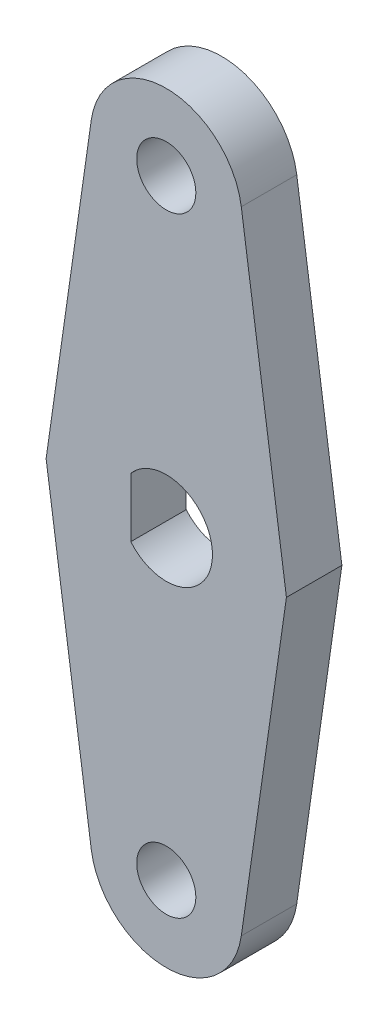
SolidWorks part; units mm, degrees
ref_plane "Alzado" through (0, 0, 0) normal (1, 0, 0) x (0, 1, 0)
ref_plane "Planta" through (0, 0, 0) normal (0, 0, 1) x (0, 1, 0)
ref_plane "Vista lateral" through (0, 0, 0) normal (0, 1, 0) x (-1, 0, 0)
sketch "Croquis1" plane through (0, 0, 0) normal (0, 0, 1) x (0, 1, 0)
  line L0 (-1.6011, 1.92) -> (1.6011, 1.92)
  line L1 (0, 6.5) -> (-17.0801, 4.0588)
  line L2 (0, -6.5) -> (-17.0801, -4.0588)
  line L3 (0, -55) -> (0, 55) construction
  line L4 (0, 6.5) -> (17.0801, 4.0588)
  line L5 (0, -6.5) -> (17.0801, -4.0588)
  circle A0 centre (0, 0) radius 2.5
  circle A1 centre (-16.5, 0) radius 1.6
  circle A2 centre (-16.5, 0) radius 4.1
  circle A3 centre (0, 0) radius 6.5
  circle A4 centre (16.5, 0) radius 4.1
  circle A5 centre (16.5, 0) radius 1.6
  point P5 (0, -2.5)
  dimension "D1" = 5
  dimension "D3" = 3.2
  dimension "D5" = 2.5
  dimension "D6" = 4
  dimension "D2" = 4.42
  dimension "D4" = 16.5
extrude "Saliente-Extruir1" add sketch "Croquis1" along normal blind 3 contours A2 A1 | A3 L1 A2 L2 | L5 A3 L4 L1 L2 A0 | L5 A4 L4 A3 | A4 A5 | L0 A0
